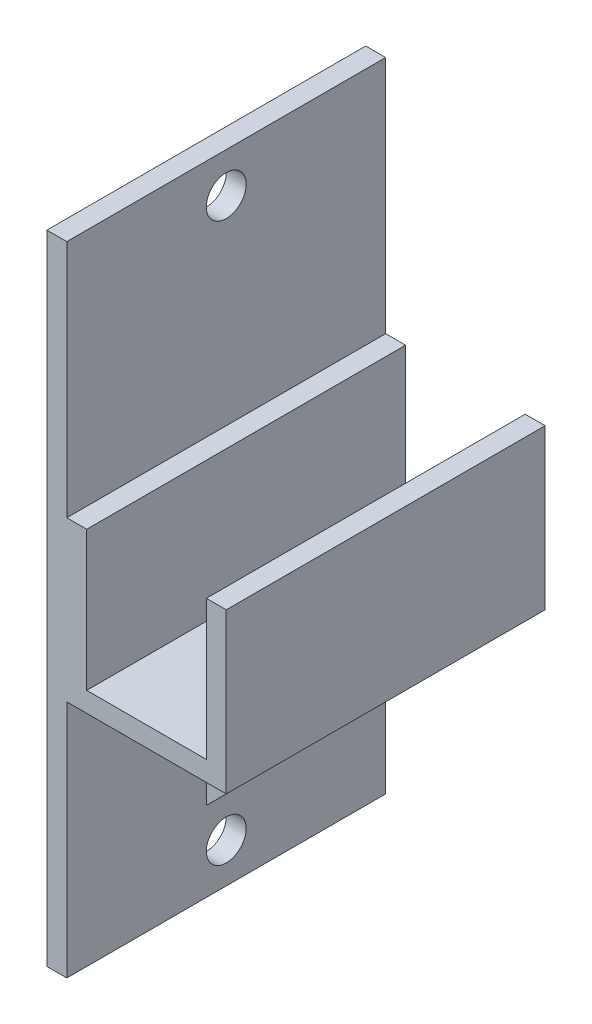
SolidWorks part; units mm, degrees
ref_plane "Front Plane" through (0, 0, 0) normal (0, 0, 1) x (1, 0, 0)
ref_plane "Top Plane" through (0, 0, 0) normal (0, 1, 0) x (1, 0, 0)
ref_plane "Right Plane" through (0, 0, 0) normal (1, 0, 0) x (0, 0, -1)
sketch "Sketch1" plane through (0, 0, 0) normal (0, 0, 1) x (1, 0, 0)
  line L0 (0, 0) -> (12.7, 0)
  line L1 (12.7, 0) -> (12.7, 25.4)
  line L2 (12.7, 25.4) -> (9.525, 25.4)
  line L3 (9.525, 25.4) -> (9.525, 3.175)
  line L4 (9.525, 3.175) -> (0, 3.175)
  line L5 (0, 3.175) -> (0, 0)
  dimension "D1" = 25.4
  dimension "D2" = 12.7
  dimension "D3" = 3.175
  dimension "D4" = 3.175
extrude "Boss-Extrude1" add sketch "Sketch1" along normal blind 50.8
mirror "Mirror1" about plane through (0, 3.175, 50.8) normal (1, 0, 0) of bodies 101
sketch "Sketch3" plane through (-12.7, 0, 0) normal (-1, 0, 0) x (0, 0, 1)
  line L0 (25.4, -38.1) -> (25.4, 0) construction
  line L1 (0, 63.5) -> (50.8, 63.5)
  line L2 (0, 63.5) -> (0, -38.1)
  line L3 (0, -38.1) -> (50.8, -38.1)
  line L4 (50.8, 63.5) -> (50.8, -38.1)
  line L5 (50.8, 0) -> (0, 0) construction
  line L6 (25.4, 63.5) -> (25.4, 25.4) construction
  line L7 (50.8, 25.4) -> (0, 25.4) construction
  circle A0 centre (25.4, 57.15) radius 3.175
  circle A1 centre (25.4, -31.75) radius 3.175
  dimension "D5" = 6.35
  dimension "D1" = 101.6
  dimension "D2" = 50.8
  dimension "D3" = 6.35
  dimension "D4" = 6.35
extrude "Boss-Extrude2" add sketch "Sketch3" along normal blind 3.175
ref_plane "Plane1" through (0, 0, 25.4) normal (0, 0, -1) x (-1, 0, 0)
sketch "Sketch4" plane through (0, 0, 25.4) normal (0, 0, -1) x (-1, 0, 0)
  line L0 (-12.7, 0) -> (12.7, -25.4)
  line L1 (12.7, 0) -> (12.7, -38.1) construction
  line L2 (12.7, 0) -> (-12.7, 0) construction
  line L3 (12.7, 0) -> (12.7, -25.4)
  line L4 (12.7, 0) -> (-12.7, 0)
  dimension "D1" = 45
extrude "Boss-Extrude3" add sketch "Sketch4" along normal blind 3.175 and the other way blind 3.175
